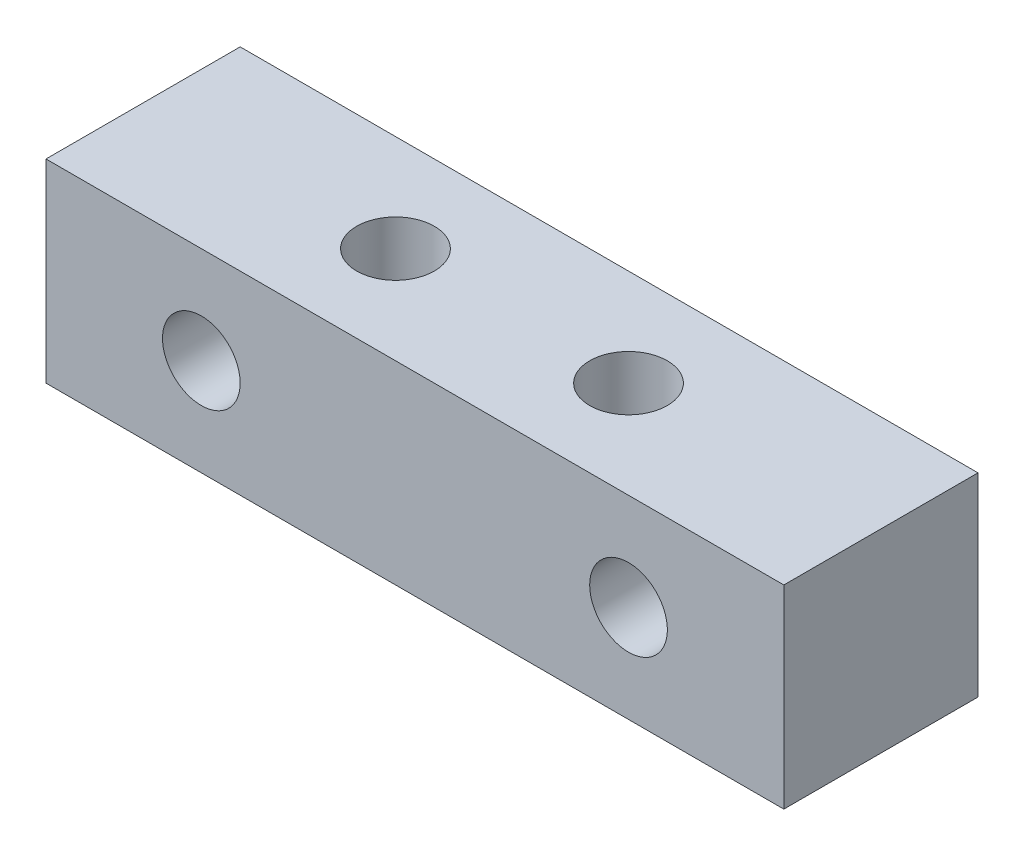
SolidWorks part; units mm, degrees
ref_plane "前视基准面" through (0, 0, 0) normal (0, 0, 1) x (1, 0, 0)
ref_plane "上视基准面" through (0, 0, 0) normal (0, 1, 0) x (1, 0, 0)
ref_plane "右视基准面" through (0, 0, 0) normal (1, 0, 0) x (0, 0, -1)
sketch "草图1" plane through (0, 0, 0) normal (0, 0, 1) x (1, 0, 0)
  line L1 (-19, -5) -> (19, -5)
  line L2 (-19, -5) -> (-19, 5)
  line L3 (-19, 5) -> (19, 5)
  line L4 (19, -5) -> (19, 5)
  line L5 (-19, -5) -> (19, 5) construction
  line L6 (-19, 5) -> (19, -5) construction
  point P0 (0, 0)
  dimension "D1" = 10
  dimension "D2" = 38
extrude "凸台-拉伸1" add sketch "草图1" along normal blind 10
sketch "草图3" plane through (0, 0, 10) normal (0, 0, 1) x (1, 0, 0)
  line L0 (0, 0) -> (0, 50000) construction
  circle A0 centre (-11, 0) radius 2
  circle A1 centre (11, 0) radius 2
  dimension "D1" = 4
  dimension "D2" = 22
extrude "切除-拉伸1" cut sketch "草图3" against normal blind 10
sketch "草图4" plane through (0, 5, 0) normal (0, 1, 0) x (1, 0, 0)
  line L0 (0, 0) -> (0, -50000) construction
  line L1 (19, 0) -> (-19, 0) construction
  line L2 (-24, -5) -> (49976, -5) construction
  line L3 (-19, -10) -> (-19, 0) construction
  circle A0 centre (-6, -5) radius 2
  circle A1 centre (6, -5) radius 2
  point P4 (0, 0)
  point P9 (-19, -5)
  dimension "D1" = 4
  dimension "D2" = 12
extrude "切除-拉伸2" cut sketch "草图4" against normal blind 10
